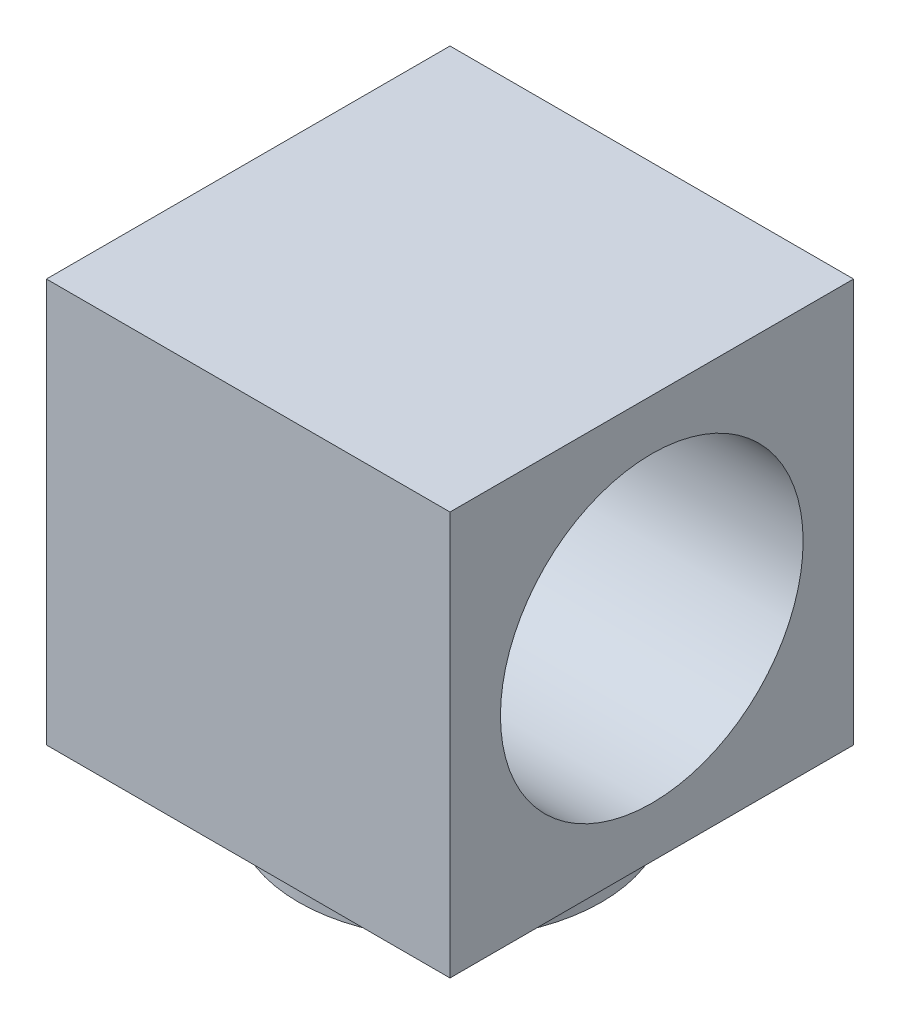
SolidWorks part; units mm, degrees
ref_plane "Front View" through (0, 0, 0) normal (0, 0, 1) x (1, 0, 0)
ref_plane "Upper View" through (0, 0, 0) normal (0, 1, 0) x (1, 0, 0)
ref_plane "Right View" through (0, 0, 0) normal (1, 0, 0) x (0, 0, -1)
sketch "Sketch1" plane through (0, 0, 0) normal (0, 0, 1) x (1, 0, 0)
  line L1 (0, 0) -> (20, 0)
  line L2 (0, 0) -> (0, 20)
  line L3 (0, 20) -> (20, 20)
  line L4 (20, 0) -> (20, 20)
extrude "Boss-Extrude1" add sketch "Sketch1" along normal blind 20
sketch "Sketch2" plane through (20, 0, 0) normal (1, 0, 0) x (0, 0, -1)
  circle A0 centre (-10, 10) radius 7.5
extrude "Cut-Extrude1" cut sketch "Sketch2" against normal blind 20
sketch "Sketch3" plane through (0, 0, 0) normal (0, -1, 0) x (-1, 0, 0)
  circle A0 centre (-10, -10) radius 7.5
  circle A1 centre (-10, -10) radius 6.5
extrude "Boss-Extrude2" add sketch "Sketch3" along normal blind 3
